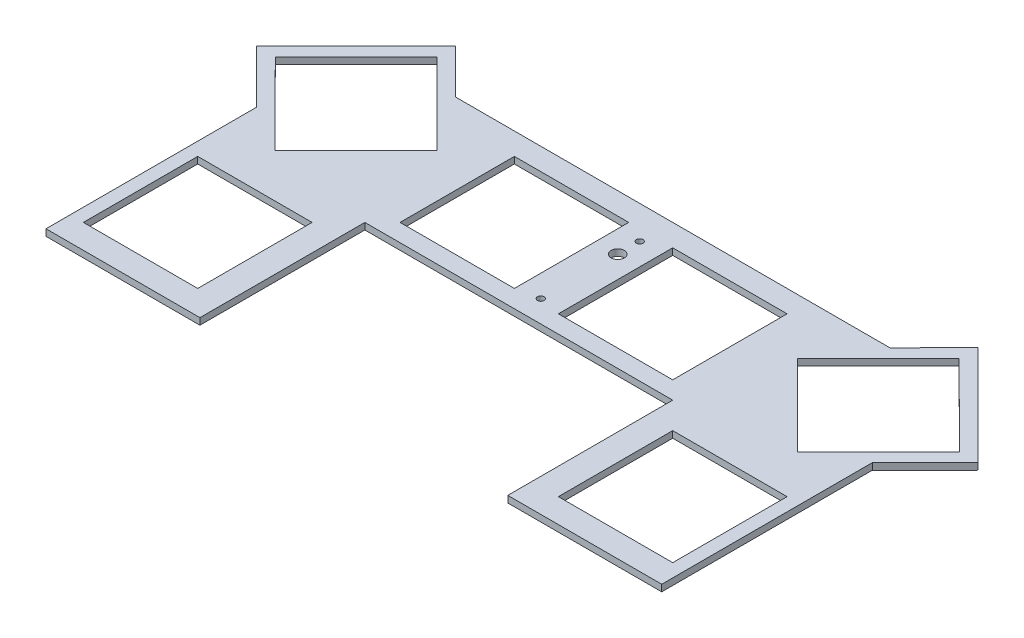
SolidWorks part; units mm, degrees
ref_plane "前视基准面" through (0, 0, 0) normal (0, 0, 1) x (1, 0, 0)
ref_plane "上视基准面" through (0, 0, 0) normal (0, 1, 0) x (1, 0, 0)
ref_plane "右视基准面" through (0, 0, 0) normal (1, 0, 0) x (0, 0, -1)
sketch "草图1" plane through (0, 0, 0) normal (0, 1, 0) x (1, 0, 0)
  line L0 (-140, -50) -> (-70, -50)
  line L1 (-82, 69.7391) -> (-118.8, 33)
  line L2 (-140, -50) -> (-140, 45.7428)
  line L3 (-98.7408, 95) -> (0, 95)
  line L4 (0, 81.5) -> (0, 95)
  line L9 (-10, 33) -> (-62, 33)
  line L10 (-10, 33) -> (-10, 85)
  line L11 (-10, 85) -> (-62, 85)
  line L12 (-62, 33) -> (-62, 85)
  line L13 (0, 25) -> (0, 33.5)
  line L14 (0, 73) -> (0, 78.5)
  line L15 (-118.8, 33) -> (-155.5391, 69.8)
  line L16 (-155.5391, 69.8) -> (-118.7391, 106.5391)
  line L17 (0, 36.5) -> (0, 67)
  line L21 (-134, 13) -> (-82, 13)
  line L22 (-134, 13) -> (-134, -39)
  line L23 (-134, -39) -> (-82, -39)
  line L24 (-82, 13) -> (-82, -39)
  line L29 (-70, -50) -> (-70, 25)
  line L30 (-70, 25) -> (0, 25)
  line L33 (-118.7391, 106.5391) -> (-82, 69.7391)
  line L34 (-118.7321, 115.0244) -> (-164.0244, 69.807)
  line L35 (-118.7321, 115.0244) -> (-98.7408, 95)
  line L36 (-164.0244, 69.807) -> (-140, 45.7428)
  arc A0 (0, 81.5) -> (0, 78.5) centre (0, 80) ccw
  arc A1 (0, 36.5) -> (0, 33.5) centre (0, 35) ccw
  arc A2 (0, 73) -> (0, 67) centre (0, 70) ccw
  dimension "D17" = 52
  dimension "D5" = 52
  dimension "D6" = 52
  dimension "D7" = 10
  dimension "D12" = 52
  dimension "D19" = 6
extrude "凸台-拉伸1" add sketch "草图1" along normal blind 3
mirror "镜向1" about plane through (0, 3, -36.5) normal (-1, 0, 0) of "凸台-拉伸1"
